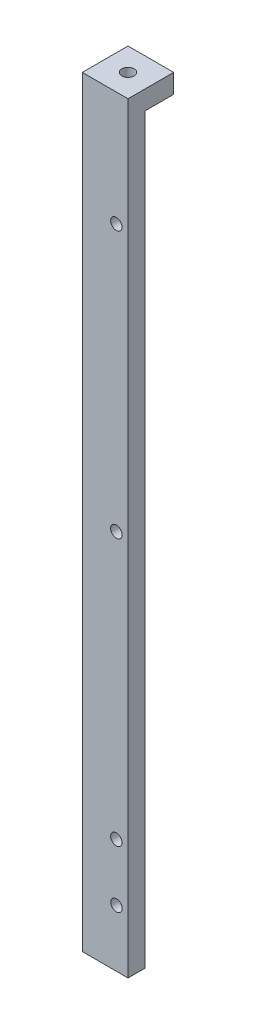
SolidWorks part; units mm, degrees
ref_plane "Front Plane" through (0, 0, 0) normal (0, 0, 1) x (1, 0, 0)
ref_plane "Top Plane" through (0, 0, 0) normal (0, 1, 0) x (1, 0, 0)
ref_plane "Right Plane" through (0, 0, 0) normal (1, 0, 0) x (0, 0, -1)
sketch "Sketch1" plane through (0, 0, 0) normal (0, 1, 0) x (1, 0, 0)
  line L1 (-6, 6) -> (-1.5, 6)
  line L2 (-6, 6) -> (-6, -6)
  line L3 (-6, -6) -> (6, -6)
  line L4 (6, -1.5) -> (6, -6)
  line L5 (0, -1.5) -> (6, -1.5)
  line L6 (-1.5, 0) -> (-1.5, 6)
  arc A0 (-1.5, 0) -> (0, -1.5) centre (0, 0) ccw
  point P0 (0, 0)
  dimension "D3" = 3
  dimension "D1" = 12
  dimension "D2" = 12
  dimension "D4" = 6
  dimension "D5" = 6
extrude "Boss-Extrude1" add sketch "Sketch1" along normal blind 200
sketch "Sketch2" plane through (0, 200, 0) normal (0, 1, 0) x (1, 0, 0)
  line L1 (-6, 6) -> (6, 6)
  line L2 (-6, 6) -> (-6, -6)
  line L3 (-6, -6) -> (6, -6)
  line L4 (6, 6) -> (6, -6)
  line L5 (-6, 6) -> (6, -6) construction
  line L6 (-6, -6) -> (6, 6) construction
  point P0 (0, 0)
extrude "Boss-Extrude2" add sketch "Sketch2" against normal blind 5
sketch "Sketch3" plane through (0, 200, 0) normal (0, 1, 0) x (1, 0, 0)
  circle A0 centre (0, 0) radius 1.625
  dimension "D1" = 3.25
extrude "Cut-Extrude1" cut sketch "Sketch3" against normal blind 15
sketch "Sketch6" plane through (0, 200, 0) normal (0, 1, 0) x (1, 0, 0)
  circle A0 centre (0, 0) radius 3
  dimension "D1" = 6
extrude "Cut-Extrude3" cut sketch "Sketch6" against normal blind 15 from offset 3 offset against normal yes
sketch "Sketch7" plane through (0, 0, 1.5) normal (0, 0, -1) x (-1, 0, 0)
  line L0 (-3, 0) -> (-2.5981, 182) construction
  line L1 (-6, 0) -> (0, 0) construction
  circle A0 centre (-2.9337, 30) radius 1.5
  circle A1 centre (-2.9337, 100) radius 1.5
  circle A2 centre (-2.9337, 170) radius 1.5
  circle A3 centre (-2.9669, 15) radius 1.5
  dimension "D1" = 3
  dimension "D4" = 3
  dimension "D5" = 15
  dimension "D2" = 30
  dimension "D3" = 3
extrude "Cut-Extrude4" cut sketch "Sketch7" against normal blind 8
sketch "Sketch8" plane through (-1.5, 0, 0) normal (1, 0, 0) x (0, 0, -1)
  line L0 (3, 0) -> (2.5981, 195) construction
  line L1 (0, 0) -> (6, 0) construction
  line L2 (2.5981, 195) -> (6, 195) construction
  line L3 (2.5981, 195) -> (2.5981, 182) construction
  circle A0 centre (2.9382, 30) radius 1.5
  circle A1 centre (2.9382, 100) radius 1.5
  circle A2 centre (2.9382, 170) radius 1.5
  circle A3 centre (2.9669, 15) radius 1.5
  dimension "D2" = 3
  dimension "D4" = 15
  dimension "D1" = 30
  dimension "D3" = 3
extrude "Cut-Extrude5" cut sketch "Sketch8" against normal blind 8
